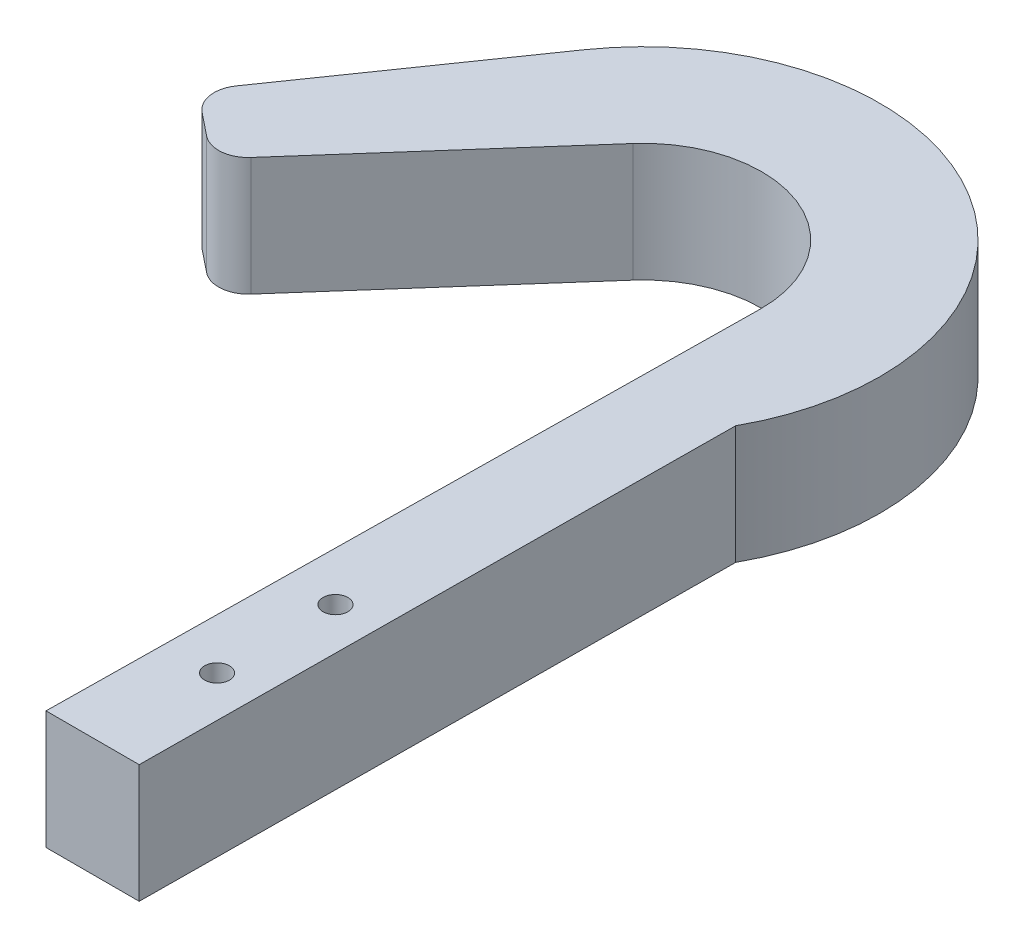
SolidWorks part; units mm, degrees
ref_plane "Front Plane" through (0, 0, 0) normal (0, 0, 1) x (1, 0, 0)
ref_plane "Top Plane" through (0, 0, 0) normal (0, 1, 0) x (1, 0, 0)
ref_plane "Right Plane" through (0, 0, 0) normal (1, 0, 0) x (0, 0, -1)
sketch "Sketch1" plane through (0, 0, 0) normal (0, 1, 0) x (1, 0, 0)
  line L12 (-73.8167, -45.8283) -> (-53.8167, -45.8283)
  line L13 (-53.8167, -45.8283) -> (-52.797, 81.1717)
  line L14 (-116.2977, 122.5706) -> (-154.6795, 79.0002)
  line L17 (-138.9596, 134.7631) -> (-169.5469, 90.7313)
  line L18 (-168.2991, 82.1505) -> (-163.4118, 78.2396)
  line L19 (-71.8404, 105.449) -> (-73.8167, -45.8283)
  arc A4 (-52.797, 81.1717) -> (-138.9596, 134.7631) centre (-97.2383, 105.7809) ccw
  arc A5 (-71.8404, 105.449) -> (-116.2977, 122.5706) centre (-97.2383, 105.7809) ccw
  arc A7 (-154.6795, 79.0002) -> (-163.4118, 78.2396) centre (-159.4444, 83.1977) cw
  arc A8 (-169.5469, 90.7313) -> (-168.2991, 82.1505) centre (-164.3317, 87.1085) ccw
  dimension "D3" = 25.4
  dimension "D4" = 50.8
  dimension "D5" = 6.35
  dimension "D6" = 6.35
  dimension "D1" = 127
  dimension "D2" = 20
extrude "Boss-Extrude1" add sketch "Sketch1" along normal blind 25.4
sketch "Sketch2" plane through (0, 0, 0) normal (0, -1, 0) x (-1, 0, 0)
  line L0 (53.8167, -45.8283) -> (52.797, 81.1717) construction
  line L1 (73.8167, -45.8283) -> (53.8167, -45.8283) construction
  line L2 (62.5031, 4.9717) -> (62.5031, -20.4283) construction
  circle A0 centre (62.5031, 4.9717) radius 2.667
  circle A1 centre (62.5031, -20.4283) radius 2.667
  dimension "D1" = 25.4
  dimension "D2" = 5.334
  dimension "D3" = 8.89
  dimension "D5" = 25.4
extrude "Cut-Extrude1" cut sketch "Sketch2" against normal blind 25.4
